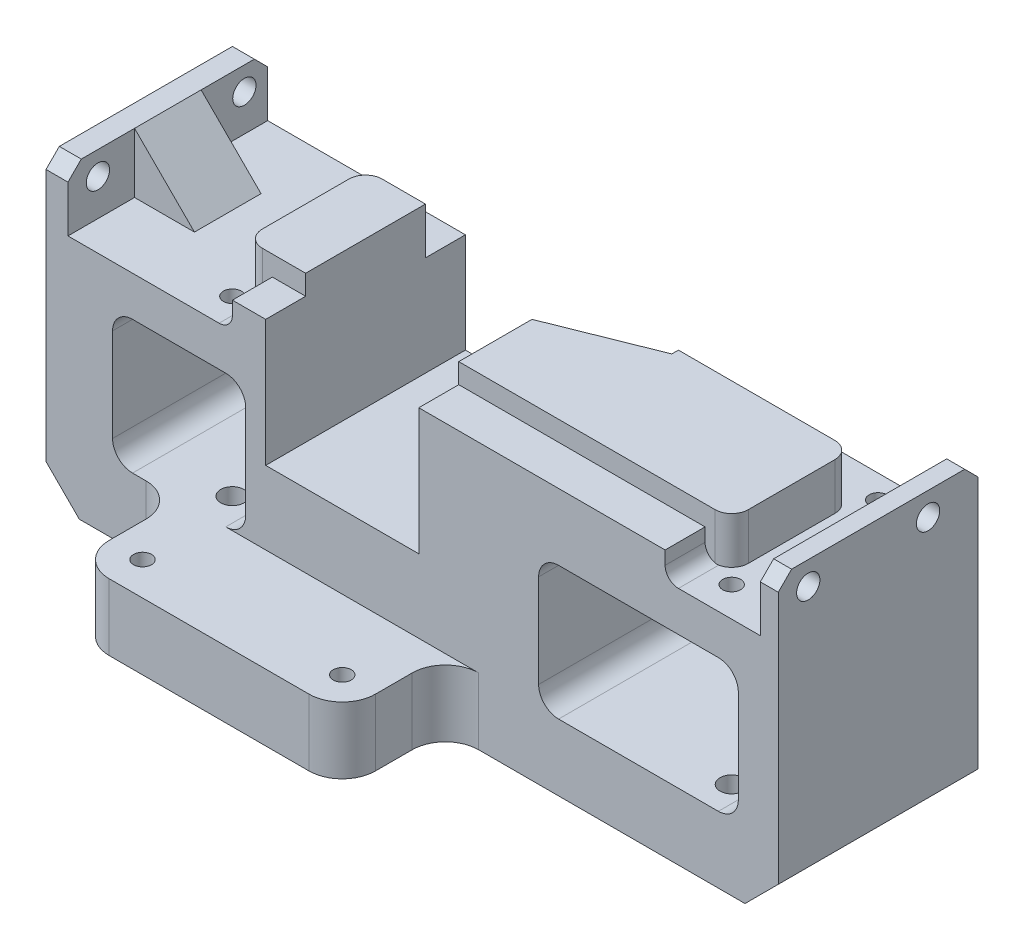
SolidWorks part; units mm, degrees
ref_plane "前视基准面" through (0, 0, 0) normal (0, 0, 1) x (1, 0, 0)
ref_plane "上视基准面" through (0, 0, 0) normal (0, 1, 0) x (1, 0, 0)
ref_plane "右视基准面" through (0, 0, 0) normal (1, 0, 0) x (0, 0, -1)
sketch "草图1" plane through (0, 0, 0) normal (0, 1, 0) x (1, 0, 0)
  line L0 (10, 15) -> (55, 15)
  line L1 (-55, -15) -> (-40, -15)
  line L2 (-55, -15) -> (-55, 15)
  line L3 (-55, 15) -> (-40, 15)
  line L4 (55, -15) -> (55, 15)
  line L5 (-55, -15) -> (55, 15) construction
  line L6 (-55, 15) -> (55, -15) construction
  line L7 (10, -15) -> (55, -15)
  line L8 (-35, 20) -> (-35, 22)
  line L9 (-35, 22) -> (5, 22)
  line L10 (5, 20) -> (5, 22)
  line L11 (-30, 14.5) -> (0, 14.5) construction
  line L12 (-30, 14.5) -> (-30, -25.5) construction
  line L13 (-30, -25.5) -> (0, -25.5) construction
  line L14 (0, 14.5) -> (0, -25.5) construction
  line L16 (-35, -20) -> (-35, -25.5)
  line L17 (-30, -30.5) -> (0, -30.5)
  line L18 (5, -20) -> (5, -25.5)
  arc A0 (10, 15) -> (5, 20) centre (10, 20) cw
  arc A1 (-40, 15) -> (-35, 20) centre (-40, 20) ccw
  circle A2 centre (-30, 14.5) radius 1.35
  circle A3 centre (0, 14.5) radius 1.35
  circle A4 centre (0, -25.5) radius 1.35
  circle A5 centre (-30, -25.5) radius 1.35
  arc A6 (0, -30.5) -> (5, -25.5) centre (0, -25.5) ccw
  arc A7 (-35, -25.5) -> (-30, -30.5) centre (-30, -25.5) ccw
  arc A8 (-40, -15) -> (-35, -20) centre (-40, -20) cw
  arc A9 (10, -15) -> (5, -20) centre (10, -20) ccw
  point P0 (0, 0)
  point P12 (5, 15)
  point P23 (-15, 14.5)
  point P24 (-15, 22)
  point P29 (-35, 21)
  point P30 (0, 0)
  dimension "D6" = 5
  dimension "D10" = 2.7
  dimension "D12" = 5
  dimension "D1" = 30
  dimension "D2" = 110
  dimension "D3" = 40
  dimension "D4" = 7
  dimension "D5" = 20
  dimension "D7" = 7.5
  dimension "D8" = 30
  dimension "D9" = 40
  dimension "D11" = 5
extrude "凸台-拉伸1" add sketch "草图1" along normal blind 10
sketch "草图2" plane through (0, 10, 0) normal (0, 1, 0) x (1, 0, 0)
  line L1 (-55, 15) -> (55, 15)
  line L2 (-55, 15) -> (-55, -15)
  line L3 (-55, -15) -> (55, -15)
  line L4 (55, 15) -> (55, -15)
extrude "凸台-拉伸2" add sketch "草图2" along normal blind 26
sketch "草图3" plane through (0, 0, 15) normal (0, 0, 1) x (1, 0, 0)
  line L0 (-40, 10) -> (10, 10) construction
  line L1 (-42, 30) -> (-28, 30)
  line L2 (-45, 27) -> (-45, 13)
  line L3 (-42, 10) -> (-28, 10)
  line L4 (-25, 27) -> (-25, 13)
  line L5 (22, 10) -> (46, 10)
  line L6 (19, 13) -> (19, 27)
  line L7 (22, 30) -> (46, 30)
  line L8 (49, 13) -> (49, 27)
  line L9 (-30, 10) -> (-35, 10) construction
  line L10 (-55, 36) -> (-55, 0) construction
  line L11 (55, 36) -> (55, 0) construction
  arc A0 (49, 13) -> (46, 10) centre (46, 13) cw
  arc A1 (46, 30) -> (49, 27) centre (46, 27) cw
  arc A2 (19, 27) -> (22, 30) centre (22, 27) cw
  arc A3 (22, 10) -> (19, 13) centre (22, 13) cw
  arc A4 (-28, 10) -> (-25, 13) centre (-28, 13) ccw
  arc A5 (-45, 13) -> (-42, 10) centre (-42, 13) ccw
  arc A6 (-42, 30) -> (-45, 27) centre (-42, 27) ccw
  arc A7 (-28, 30) -> (-25, 27) centre (-28, 27) cw
  point P10 (-31.6512, 10)
  point P19 (49, 10)
  point P22 (49, 30)
  point P27 (19, 10)
  point P30 (-25, 10)
  point P33 (-45, 10)
  point P36 (-45, 30)
  dimension "D7" = 3
  dimension "D1" = 10
  dimension "D2" = 20
  dimension "D3" = 20
  dimension "D4" = 30
  dimension "D5" = 6
  dimension "D6" = 20
extrude "切除-拉伸1" cut sketch "草图3" against normal through all
sketch "草图4" plane through (0, 36, 0) normal (0, 1, 0) x (1, 0, 0)
  line L0 (55, -15) -> (55, 15) construction
  line L1 (-28.5, 9) -> (39.5, 9)
  line L2 (-31, 6.5) -> (-31, -6.5)
  line L3 (-28.5, -9) -> (39.5, -9)
  line L4 (42, 6.5) -> (42, -6.5)
  line L5 (-55, -15) -> (55, -15) construction
  arc A0 (-28.5, 9) -> (-31, 6.5) centre (-28.5, 6.5) ccw
  arc A1 (-31, -6.5) -> (-28.5, -9) centre (-28.5, -6.5) ccw
  arc A2 (39.5, -9) -> (42, -6.5) centre (39.5, -6.5) ccw
  arc A3 (39.5, 9) -> (42, 6.5) centre (39.5, 6.5) cw
  point P12 (-31, -9)
  point P15 (42, -9)
  point P18 (42, 9)
  dimension "D5" = 2.5
  dimension "D1" = 13
  dimension "D2" = 6
  dimension "D3" = 18
  dimension "D4" = 73
extrude "凸台-拉伸3" add sketch "草图4" along normal blind 7
sketch "草图5" plane through (0, 36, 0) normal (0, 1, 0) x (1, 0, 0)
  line L0 (55, -15) -> (55, 15) construction
  line L1 (-31.5, 11.5) -> (43.5, 11.5) construction
  line L2 (-31.5, 11.5) -> (-31.5, -10.5) construction
  line L3 (-31.5, -10.5) -> (43.5, -10.5) construction
  line L4 (43.5, 11.5) -> (43.5, -10.5) construction
  line L5 (-55, -15) -> (55, -15) construction
  circle A0 centre (43.5, 11.5) radius 1.35
  circle A1 centre (43.5, -10.5) radius 1.35
  circle A2 centre (-31.5, -10.5) radius 1.35
  circle A3 centre (-31.5, 11.5) radius 1.35
  dimension "D1" = 2.7
  dimension "D2" = 22
  dimension "D3" = 75
  dimension "D4" = 11.5
  dimension "D5" = 4.5
extrude "切除-拉伸2" cut sketch "草图5" against normal blind 7
sketch "草图6" plane through (0, 36, 0) normal (0, 1, 0) x (1, 0, 0)
  line L0 (-28.5, -9) -> (39.5, -9) construction
  line L1 (-27, -9) -> (38, -9)
  line L2 (-27, -9) -> (-27, -15)
  line L3 (-27, -15) -> (38, -15)
  line L4 (38, -9) -> (38, -15)
  line L5 (-55, -15) -> (55, -15) construction
  circle A0 centre (43.5, -10.5) radius 1.35 construction
  dimension "D1" = 65
  dimension "D2" = 5.5
extrude "凸台-拉伸4" add sketch "草图6" along normal blind 4
sketch "草图7" plane through (0, 36, 0) normal (0, 1, 0) x (1, 0, 0)
  line L0 (-55, -15) -> (-27, -15) construction
  line L1 (-55, 15) -> (-51.7, 15)
  line L2 (-55, 15) -> (-55, -15)
  line L3 (-55, -15) -> (-51.7, -15)
  line L4 (-51.7, 15) -> (-51.7, -15)
  line L5 (38, -15) -> (55, -15) construction
  line L6 (55, 15) -> (52.3, 15)
  line L7 (55, 15) -> (55, -15)
  line L8 (55, -15) -> (52.3, -15)
  line L9 (52.3, 15) -> (52.3, -15)
  dimension "D1" = 104
  dimension "D2" = 3.3
extrude "凸台-拉伸5" add sketch "草图7" along normal blind 9
sketch "草图8" plane through (0, 0, 0) normal (0, 0, 1) x (1, 0, 0)
  line L0 (-51.7, 45) -> (-42.7, 36)
  line L1 (-51.7, 36) -> (-27, 36) construction
  dimension "D1" = 45
rib "筋1" sketch "草图8" sketch "草图8" thickness 10 extrusion direction parallel to sketch draft on no parameters "D1"=10
sketch "草图9" plane through (0, 0, 0) normal (0, 0, 1) x (1, 0, 0)
  line L0 (52.3, 45) -> (47.1038, 36)
  line L1 (38, 36) -> (52.3, 36) construction
  line L2 (52.3, 45) -> (52.3, 36) construction
  dimension "D1" = 30
rib "筋2" sketch "草图9" sketch "草图9" thickness 10 extrusion direction parallel to sketch draft on no parameters "D1"=10
sketch "草图10" plane through (55, 0, 0) normal (1, 0, 0) x (0, 0, -1)
  line L0 (-10.5, 41.5) -> (7.5, 41.5) construction
  line L1 (-15, 45) -> (-15, 0) construction
  line L2 (-5, 36) -> (-15, 36) construction
  circle A0 centre (-10.5, 41.5) radius 1.75
  circle A1 centre (7.5, 41.5) radius 1.75
  dimension "D2" = 3.5
  dimension "D3" = 4.5
  dimension "D1" = 18
  dimension "D4" = 5.5
extrude "切除-拉伸3" cut sketch "草图10" against normal up to next
sketch "草图11" plane through (-55, 0, 0) normal (-1, 0, 0) x (0, 0, 1)
  circle A0 centre (10.5, 41.5) radius 1.75 construction
  circle A1 centre (10.5, 41.5) radius 1.75
  circle A2 centre (-11.5, 41.5) radius 1.75
  point P5 (0, 0)
  dimension "D1" = 22
extrude "切除-拉伸4" cut sketch "草图11" against normal up to next
fillet "圆角1" radius 2 2 edges at (-27, 36, 12) (38, 36, 12)
sketch "草图12" plane through (0, 43, 0) normal (0, 1, 0) x (1, 0, 0)
  line L0 (-22, -15) -> (-22, 15)
  line L1 (-28, -15) -> (10, -15) construction
  line L2 (52.3, 15) -> (-51.7, 15) construction
  line L3 (-22, 15) -> (16, 15)
  line L4 (16, 15) -> (16, 8)
  line L5 (16, 8) -> (1, 2)
  line L6 (1, 2) -> (1, -15)
  line L7 (-27, -15) -> (38, -15) construction
  line L8 (1, -15) -> (-22, -15)
  line L9 (-55, 15) -> (-55, -15) construction
  dimension "D1" = 33
  dimension "D2" = 23
  dimension "D3" = 38
  dimension "D4" = 7
  dimension "D5" = 17
extrude "切除-拉伸5" cut sketch "草图12" against normal blind 22
chamfer "倒角1" distance 5 angle 45 1 edges at (-55, 0, 0)
chamfer "倒角2" distance 2 angle 45 4 edges at (53.65, 45, 15) (53.65, 45, -15) (-53.35, 45, -15) (-53.35, 45, 15)
sketch "草图13" plane through (0, 10, 0) normal (0, 1, 0) x (1, 0, 0)
  circle A0 centre (43.5, 11.5) radius 1.75
  circle A1 centre (43.5, -10.5) radius 1.75
  circle A2 centre (-31.5, 11.5) radius 1.75
  circle A3 centre (-31.5, -10.5) radius 1.75
  dimension "D1" = 3.5
extrude "切除-拉伸6" cut sketch "草图13" against normal through all
chamfer "倒角3" distance 5 angle 45 1 edges at (55, 0, 0)
sketch "草图14" plane through (0, 0, 0) normal (0, -1, 0) x (1, 0, 0)
  line L0 (55, 15) -> (55, -15) construction
  line L1 (5, -22) -> (-35, -22) construction
  circle A0 centre (20, -14.5) radius 3
  dimension "D1" = 35
  dimension "D2" = 7.5
  dimension "D3" = 6
extrude "切除-拉伸7" cut sketch "草图14" against normal blind 4
